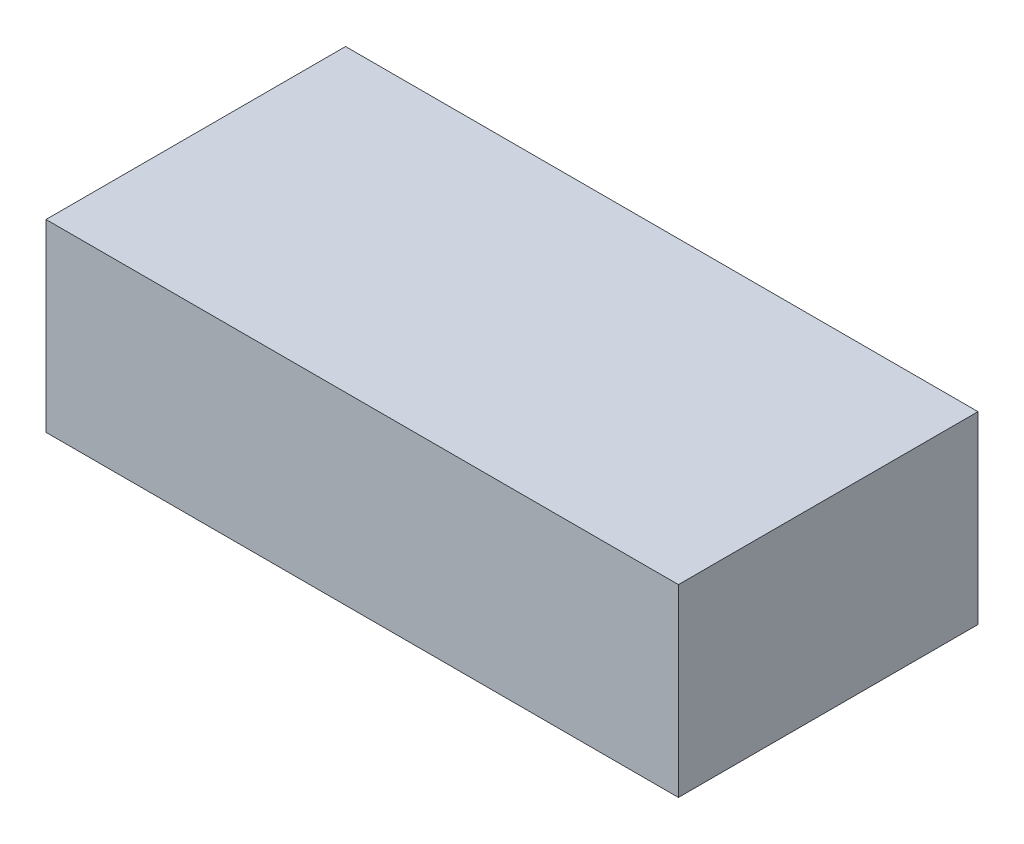
SolidWorks part; units mm, degrees
ref_plane "Front Plane" through (0, 0, 0) normal (0, 0, 1) x (1, 0, 0)
ref_plane "Top Plane" through (0, 0, 0) normal (0, 1, 0) x (1, 0, 0)
ref_plane "Right Plane" through (0, 0, 0) normal (1, 0, 0) x (0, 0, -1)
sketch "Sketch1" plane through (0, 0, 0) normal (0, 1, 0) x (1, 0, 0)
  line L1 (-52.5851, 24.3497) -> (60.6153, 24.3497)
  line L2 (-52.5851, 24.3497) -> (-52.5851, -29.2715)
  line L3 (-52.5851, -29.2715) -> (60.6153, -29.2715)
  line L4 (60.6153, 24.3497) -> (60.6153, -29.2715)
extrude "Boss-Extrude1" add sketch "Sketch1" along normal blind 33
